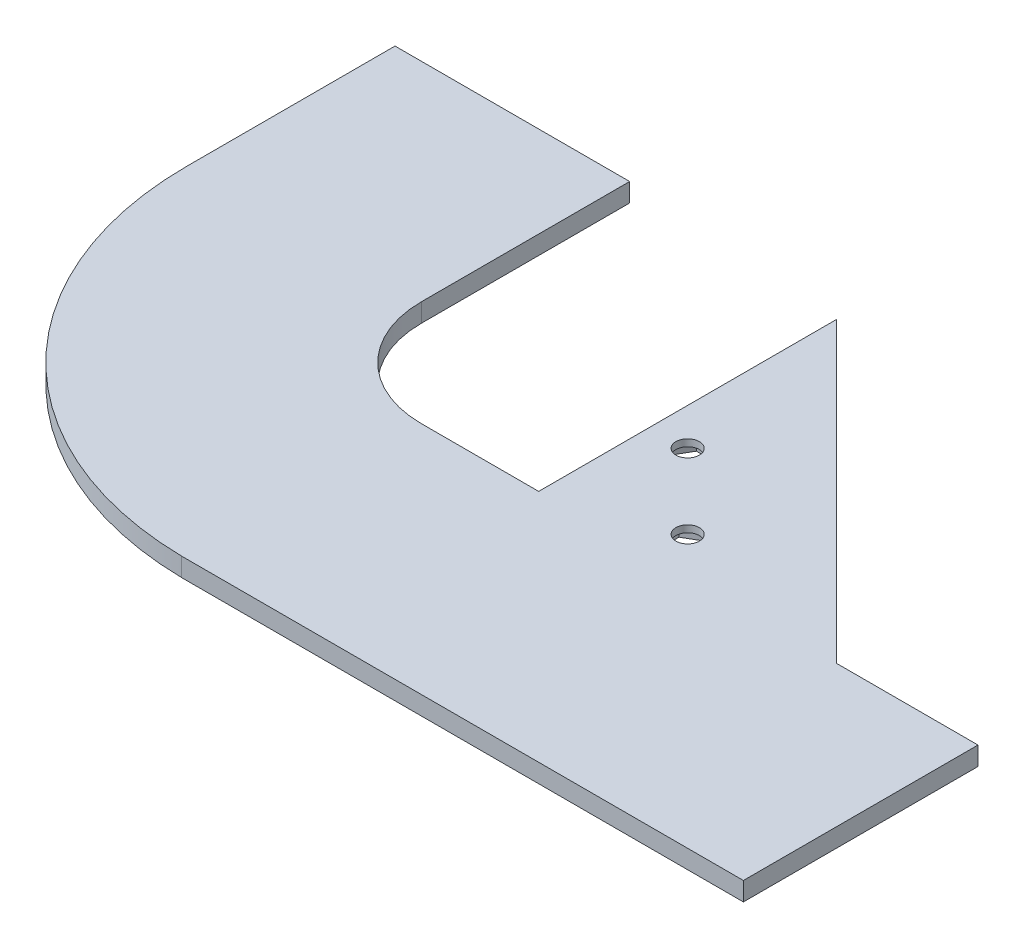
SolidWorks part; units mm, degrees
ref_plane "Front" through (0, 0, 0) normal (0, 0, 1) x (1, 0, 0)
ref_plane "Top" through (0, 0, 0) normal (0, 1, 0) x (1, 0, 0)
ref_plane "Right" through (0, 0, 0) normal (1, 0, 0) x (0, 0, -1)
sketch "Sketch1" plane through (0, 0, 0) normal (0, 1, 0) x (1, 0, 0)
  line L0 (0, 0) -> (50.8, 0)
  line L1 (-21.723, 0) -> (21.723, 0) construction
  line L2 (50.8, 0) -> (0, 50.8)
  line L3 (0, -27.94) -> (0, 27.94) construction
  line L4 (0, 50.8) -> (0, 0)
  dimension "D1" = 50.8
  dimension "D2" = 50.8
extrude "Boss-Extrude1" add sketch "Sketch1" along normal blind 3.175 contours L2 L4 L0
sketch "Sketch2" plane through (0, 3.175, 0) normal (0, 1, 0) x (1, 0, 0)
  line L0 (0, -1.7463) -> (0, 1.7463) construction
  line L1 (-1.7463, 0) -> (1.7463, 0) construction
  line L2 (0, 0) -> (25.4, 25.4) construction
  line L3 (50.8, 0) -> (0, 50.8) construction
  circle A0 centre (19.05, 6.35) radius 2
  circle A1 centre (6.35, 19.05) radius 2
  dimension "D1" = 4
  dimension "D3" = 6.35
  dimension "D2" = 19.05
extrude "Cut-Extrude1" cut sketch "Sketch2" against normal through all contours A0 | A1
sketch "Sketch3" plane through (0, 3.175, 0) normal (0, 1, 0) x (1, 0, 0)
  line L0 (0, 0) -> (25.4, 25.4) construction
  line L1 (8.3707, 15.55) -> (10.3914, 19.05)
  line L2 (10.3914, 19.05) -> (8.3707, 22.55)
  line L3 (0, 0) -> (50.8, 0)
  line L4 (50.8, 0) -> (0, 50.8)
  line L5 (0, 50.8) -> (0, 0)
  line L6 (0, 0) -> (50.8, 0)
  line L7 (50.8, 0) -> (0, 50.8)
  line L8 (0, 50.8) -> (0, 0)
  line L9 (8.3707, 22.55) -> (4.3293, 22.55)
  line L10 (4.3293, 22.55) -> (2.3086, 19.05)
  line L11 (2.3086, 19.05) -> (4.3293, 15.55)
  line L12 (4.3293, 15.55) -> (8.3707, 15.55)
  line L13 (22.55, 4.3293) -> (19.05, 2.3086)
  line L14 (19.05, 2.3086) -> (15.55, 4.3293)
  line L15 (15.55, 4.3293) -> (15.55, 8.3707)
  line L16 (15.55, 8.3707) -> (19.05, 10.3914)
  line L17 (19.05, 10.3914) -> (22.55, 8.3707)
  line L18 (22.55, 8.3707) -> (22.55, 4.3293)
  circle A0 centre (6.35, 19.05) radius 2 construction
  circle A1 centre (6.35, 19.05) radius 2
  circle A2 centre (19.05, 6.35) radius 2 construction
  circle A3 centre (19.05, 6.35) radius 2
  circle A4 centre (6.35, 19.05) radius 3.5 construction
  dimension "D2" = 7
  dimension "D1" = 0
extrude "Cut-Extrude2" cut sketch "Sketch3" along normal blind 2 from surface at -3.175 contours L2 L9 L10 L11 L12 L1 | L17 L18 L13 L14 L15 L16 starting at face at (6.35, 0, -21.05)
sketch "Sketch4" plane through (0, 0, 0) normal (0, -1, 0) x (-1, 0, 0)
  line L0 (0, 0) -> (-25.4, 25.4) construction
  line L1 (-50.8, 0) -> (0, 50.8) construction
  line L2 (0, 0) -> (-74.9046, 0)
  line L3 (-74.9046, 0) -> (-74.9046, -40)
  line L4 (-1.7463, 0) -> (1.7463, 0) construction
  line L5 (-74.9046, -40) -> (20.8712, -40)
  line L6 (0, 0) -> (20, 0)
  line L7 (20, 0) -> (20, 18) construction
  line L8 (38, 18) -> (38, 53.5115)
  line L9 (38, 53.5115) -> (78.0065, 53.5115)
  line L10 (78.0065, 53.5115) -> (78.0065, 18)
  line L11 (0, 1.7463) -> (0, -1.7463) construction
  arc A0 (20, 0) -> (38, 18) centre (20, 18) ccw
  arc A1 (20.8712, -40) -> (78.0065, 18) centre (20, 18) ccw
  dimension "D1" = 40
  dimension "D2" = 18
  dimension "D3" = 20
extrude "Boss-Extrude2" add sketch "Sketch4" against normal through all
